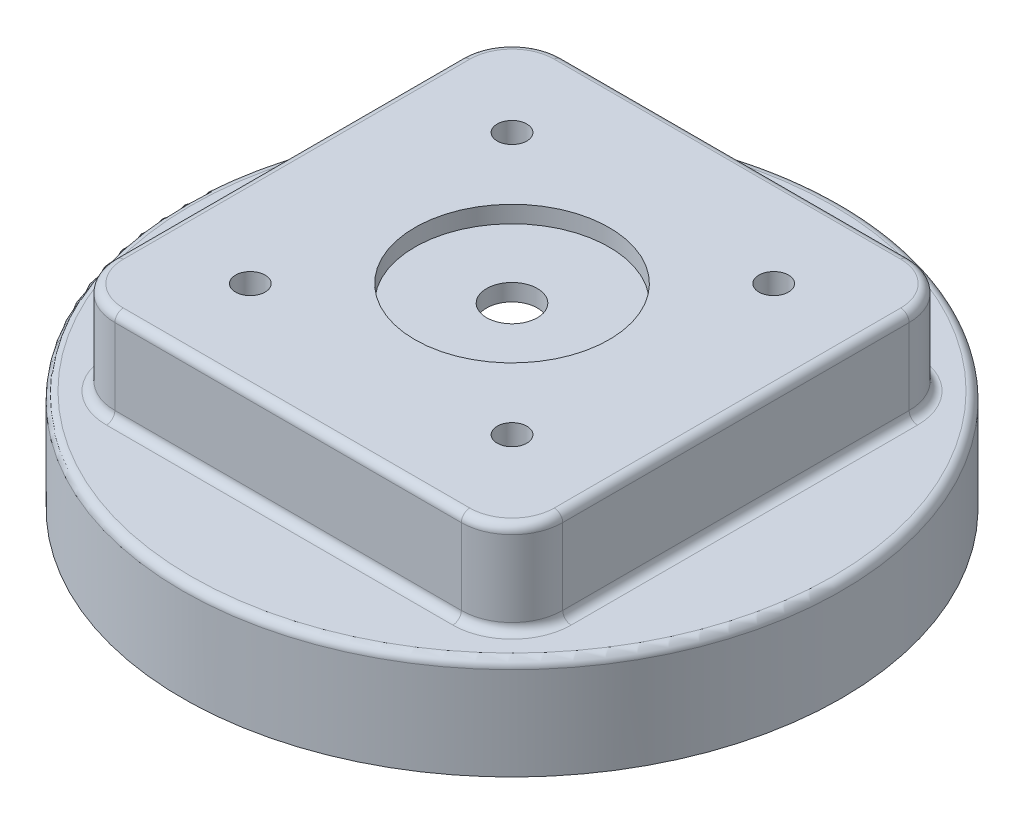
SolidWorks part; units mm, degrees
material "Acrylic (Medium-high impact)"
ref_plane "Front Plane" through (0, 0, 0) normal (0, 0, 1) x (1, 0, 0)
ref_plane "Top Plane" through (0, 0, 0) normal (0, 1, 0) x (1, 0, 0)
ref_plane "Right Plane" through (0, 0, 0) normal (1, 0, 0) x (0, 0, -1)
sketch "Sketch1" plane through (0, 0, 0) normal (0, 1, 0) x (1, 0, 0)
  circle A0 centre (0, 0) radius 35.5
  circle A1 centre (0, 0) radius 39
  dimension "D1" = 71
  dimension "D2" = 78
extrude "Boss-Extrude1" add sketch "Sketch1" along normal blind 8
sketch "Sketch2" plane through (0, 8, 0) normal (0, 1, 0) x (1, 0, 0)
  line L1 (-20.5, -22.5) -> (20.5, -22.5)
  line L2 (-22.5, -20.5) -> (-22.5, 20.5)
  line L3 (-20.5, 22.5) -> (20.5, 22.5)
  line L4 (22.5, -20.5) -> (22.5, 20.5)
  line L5 (-22.5, -22.5) -> (22.5, 22.5) construction
  line L6 (-22.5, 22.5) -> (22.5, -22.5) construction
  circle A0 centre (0, 0) radius 39
  arc A1 (-20.5, -22.5) -> (-22.5, -20.5) centre (-20.5, -20.5) cw
  arc A2 (20.5, -22.5) -> (22.5, -20.5) centre (20.5, -20.5) ccw
  arc A3 (20.5, 22.5) -> (22.5, 20.5) centre (20.5, 20.5) cw
  arc A4 (-22.5, 20.5) -> (-20.5, 22.5) centre (-20.5, 20.5) cw
  dimension "D3" = 2
  dimension "D1" = 45
  dimension "D2" = 45
extrude "Boss-Extrude2" add sketch "Sketch2" along normal blind 4
sketch "Sketch3" plane through (0, 12, 0) normal (0, 1, 0) x (1, 0, 0)
  line L5 (-20.5, -22.5) -> (20.5, -22.5)
  line L6 (22.5, -20.5) -> (22.5, 20.5)
  line L7 (20.5, 22.5) -> (-20.5, 22.5)
  line L8 (-22.5, 20.5) -> (-22.5, -20.5)
  line L9 (-20.5, -26.5) -> (20.5, -26.5)
  line L10 (26.5, -20.5) -> (26.5, 20.5)
  line L11 (20.5, 26.5) -> (-20.5, 26.5)
  line L12 (-26.5, 20.5) -> (-26.5, -20.5)
  line L13 (-20.5, -26.5) -> (20.5, -26.5)
  line L14 (26.5, -20.5) -> (26.5, 20.5)
  line L15 (20.5, 26.5) -> (-20.5, 26.5)
  line L16 (-26.5, 20.5) -> (-26.5, -20.5)
  arc A6 (20.5, -22.5) -> (22.5, -20.5) centre (20.5, -20.5) ccw
  arc A7 (22.5, 20.5) -> (20.5, 22.5) centre (20.5, 20.5) ccw
  arc A8 (-20.5, 22.5) -> (-22.5, 20.5) centre (-20.5, 20.5) ccw
  arc A9 (-22.5, -20.5) -> (-20.5, -22.5) centre (-20.5, -20.5) ccw
  arc A10 (-26.5, -20.5) -> (-20.5, -26.5) centre (-20.5, -20.5) ccw
  arc A11 (20.5, -26.5) -> (26.5, -20.5) centre (20.5, -20.5) ccw
  arc A12 (26.5, 20.5) -> (20.5, 26.5) centre (20.5, 20.5) ccw
  arc A13 (-20.5, 26.5) -> (-26.5, 20.5) centre (-20.5, 20.5) ccw
  arc A14 (-26.5, -20.5) -> (-20.5, -26.5) centre (-20.5, -20.5) ccw
  arc A15 (20.5, -26.5) -> (26.5, -20.5) centre (20.5, -20.5) ccw
  arc A16 (26.5, 20.5) -> (20.5, 26.5) centre (20.5, 20.5) ccw
  arc A17 (-20.5, 26.5) -> (-26.5, 20.5) centre (-20.5, 20.5) ccw
  dimension "D1" = 4
  dimension "D2" = 4
extrude "Boss-Extrude3" add sketch "Sketch3" along normal blind 7
sketch "Sketch4" plane through (0, 19, 0) normal (0, 1, 0) x (1, 0, 0)
  line L8 (-20.5, -26.5) -> (20.5, -26.5)
  line L9 (26.5, -20.5) -> (26.5, 20.5)
  line L10 (20.5, 26.5) -> (-20.5, 26.5)
  line L11 (-26.5, 20.5) -> (-26.5, -20.5)
  line L12 (-20.5, -26.5) -> (20.5, -26.5)
  line L13 (26.5, -20.5) -> (26.5, 20.5)
  line L14 (20.5, 26.5) -> (-20.5, 26.5)
  line L15 (-26.5, 20.5) -> (-26.5, -20.5)
  arc A8 (-26.5, -20.5) -> (-20.5, -26.5) centre (-20.5, -20.5) ccw
  arc A9 (20.5, -26.5) -> (26.5, -20.5) centre (20.5, -20.5) ccw
  arc A10 (26.5, 20.5) -> (20.5, 26.5) centre (20.5, 20.5) ccw
  arc A11 (-20.5, 26.5) -> (-26.5, 20.5) centre (-20.5, 20.5) ccw
  arc A12 (-26.5, -20.5) -> (-20.5, -26.5) centre (-20.5, -20.5) ccw
  arc A13 (20.5, -26.5) -> (26.5, -20.5) centre (20.5, -20.5) ccw
  arc A14 (26.5, 20.5) -> (20.5, 26.5) centre (20.5, 20.5) ccw
  arc A15 (-20.5, 26.5) -> (-26.5, 20.5) centre (-20.5, 20.5) ccw
  dimension "D1" = 0
extrude "Boss-Extrude4" add sketch "Sketch4" along normal blind 4
sketch "Sketch5" plane through (0, 23, 0) normal (0, 1, 0) x (1, 0, 0)
  circle A0 centre (0, 0) radius 11.5
  dimension "D1" = 23
extrude "Cut-Extrude1" cut sketch "Sketch5" against normal blind 2
sketch "Sketch6" plane through (0, 23, 0) normal (0, 1, 0) x (1, 0, 0)
  line L0 (-24.7426, 24.7426) -> (24.7426, -24.7426) construction
  line L1 (-24.7426, -24.7426) -> (24.7426, 24.7426) construction
  arc A0 (-20.5, 26.5) -> (-26.5, 20.5) centre (-20.5, 20.5) ccw construction
  arc A1 (20.5, -26.5) -> (26.5, -20.5) centre (20.5, -20.5) ccw construction
  arc A2 (-26.5, -20.5) -> (-20.5, -26.5) centre (-20.5, -20.5) ccw construction
  arc A3 (26.5, 20.5) -> (20.5, 26.5) centre (20.5, 20.5) ccw construction
  circle A4 centre (0, 0) radius 21.9 construction
  circle A5 centre (-15.4856, 15.4856) radius 1.75
  circle A6 centre (15.4856, 15.4856) radius 1.75
  circle A7 centre (15.4856, -15.4856) radius 1.75
  circle A8 centre (-15.4856, -15.4856) radius 1.75
  circle A9 centre (0, 0) radius 3
  point P29 (0, 0)
  dimension "D1" = 4
  dimension "D2" = 6
  dimension "D3" = 3.5
extrude "Cut-Extrude2" cut sketch "Sketch6" against normal through all
fillet "Fillet1" radius 1 9 edges at (24.7426, 12, 24.7426) (26.5, 12, 0) (24.7426, 12, -24.7426) (0, 12, -26.5) (-24.7426, 12, -24.7426) (-26.5, 12, 0) (-24.7426, 12, 24.7426) (0, 12, 26.5) (0, 12, 39)
fillet "Fillet2" radius 1 8 edges at (-24.7426, 23, -24.7426) (0, 23, -26.5) (24.7426, 23, -24.7426) (26.5, 23, 0) (24.7426, 23, 24.7426) (0, 23, 26.5) (-24.7426, 23, 24.7426) (-26.5, 23, 0)
sketch "Sketch7" plane through (0, 0, 0) normal (1, 0, 0) x (0, 0, -1)
  line L0 (-20.5, 8) -> (20.5, 8) construction
  circle A0 centre (0, -2.75) radius 10.6
  dimension "D1" = 21.2
  dimension "D2" = 10.75
extrude "Cut-Extrude3" cut sketch "Sketch7" against normal blind 50
